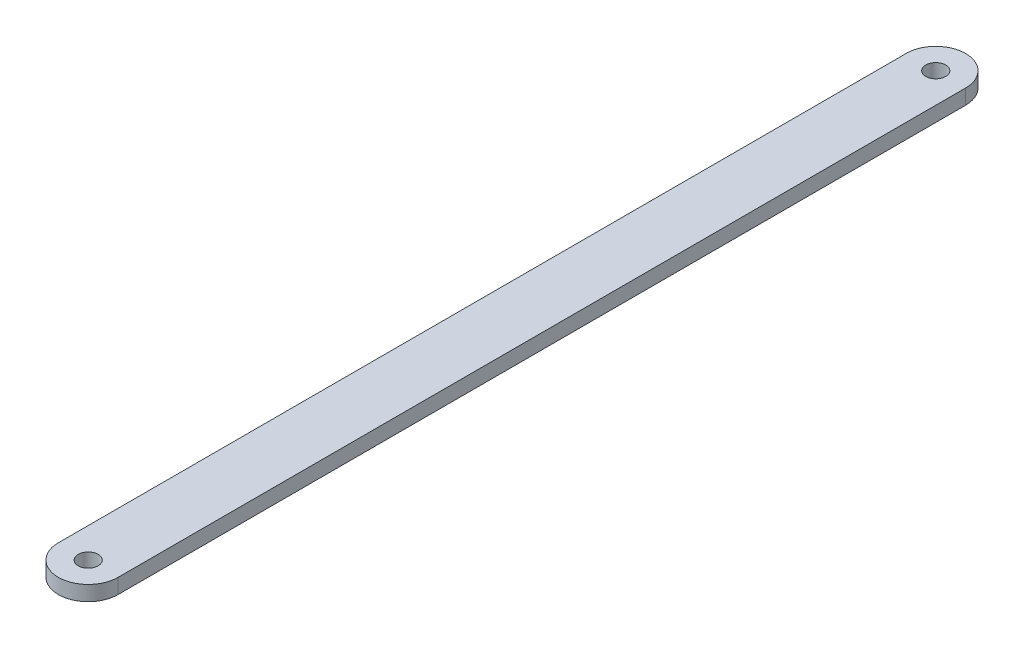
SolidWorks part; units mm, degrees
ref_plane "Front Plane" through (0, 0, 0) normal (0, 0, 1) x (1, 0, 0)
ref_plane "Top Plane" through (0, 0, 0) normal (0, 1, 0) x (1, 0, 0)
ref_plane "Right Plane" through (0, 0, 0) normal (1, 0, 0) x (0, 0, -1)
sketch "Sketch1" plane through (0, 0, 0) normal (0, 1, 0) x (1, 0, 0)
  line L0 (-6.3124, -84.9439) -> (-6.2813, 84.5738)
  line L1 (5.6876, 85.184) -> (5.6876, -84.9439)
  circle A0 centre (-0.3124, 85.184) radius 2
  circle A1 centre (-0.3124, -84.9439) radius 2
  arc A2 (5.6876, 85.184) -> (-6.2813, 84.5738) centre (-0.3124, 85.184) ccw
  arc A3 (-6.3124, -84.9417) -> (5.6876, -84.9439) centre (-0.3124, -84.9439) ccw
  dimension "D1" = 4
  dimension "D2" = 12
extrude "Boss-Extrude1" add sketch "Sketch1" along normal mid plane 3 contours L0 A3 L1 A2 A0 A1
